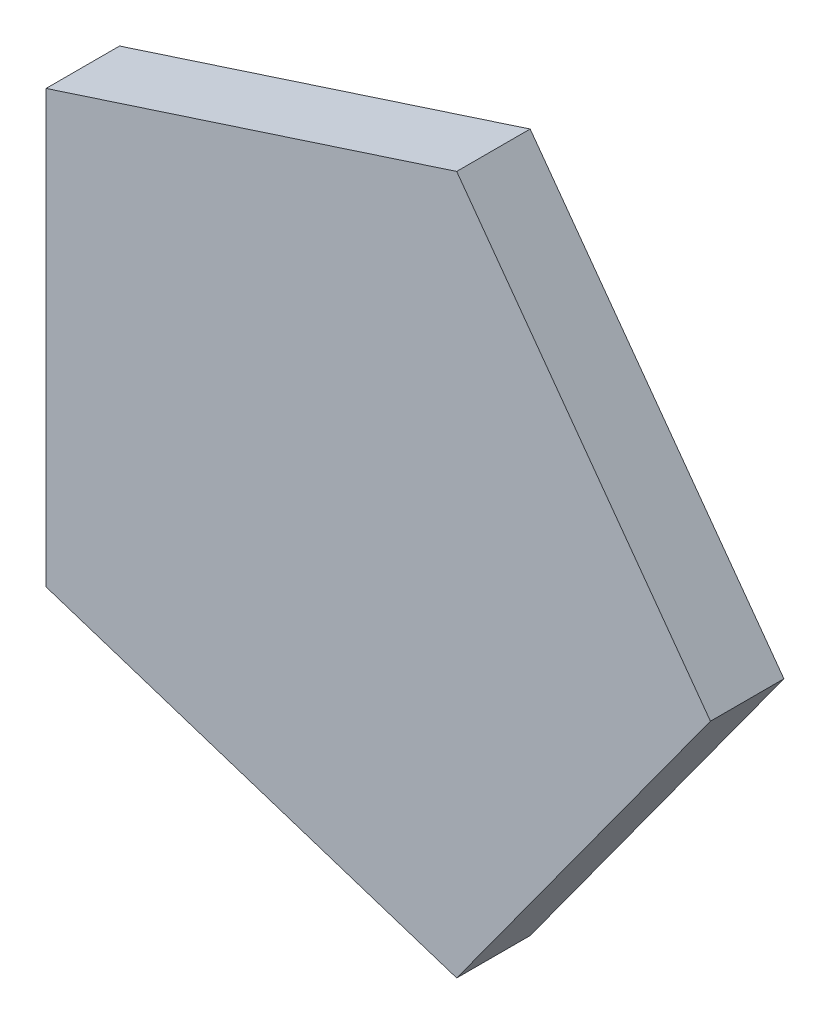
SolidWorks part; units mm, degrees
ref_plane "前视基准面" through (0, 0, 0) normal (0, 0, 1) x (1, 0, 0)
ref_plane "上视基准面" through (0, 0, 0) normal (0, 1, 0) x (1, 0, 0)
ref_plane "右视基准面" through (0, 0, 0) normal (1, 0, 0) x (0, 0, -1)
other "Configuration Table"
sketch "草图1" plane through (0, 0, 0) normal (0, 0, 1) x (1, 0, 0)
  line L1 (500, 0) -> (154.5085, 475.5283)
  line L2 (154.5085, 475.5283) -> (-404.5085, 293.8926)
  line L3 (-404.5085, 293.8926) -> (-404.5085, -293.8926)
  line L4 (-404.5085, -293.8926) -> (154.5085, -475.5283)
  line L5 (154.5085, -475.5283) -> (500, 0)
  circle A0 centre (0, 0) radius 404.5085 construction
extrude "凸台-拉伸1" add sketch "草图1" along normal blind 100
